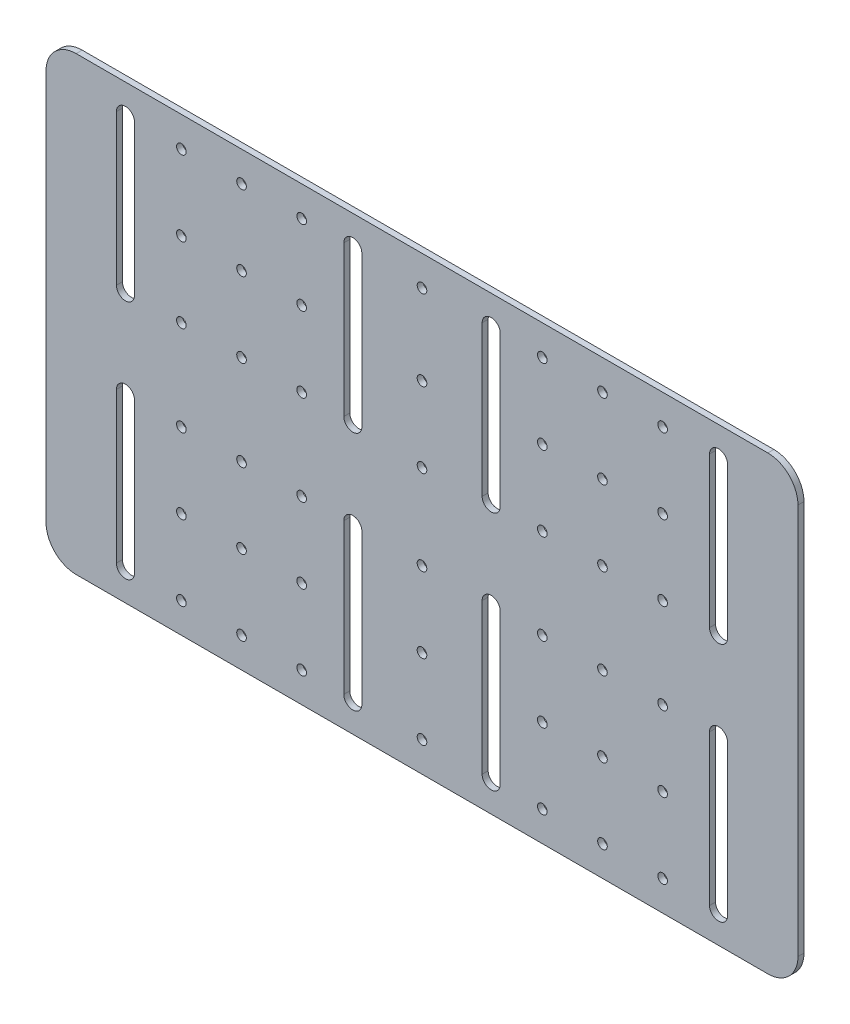
SolidWorks part; units mm, degrees
ref_plane "Front Plane" through (0, 0, 0) normal (0, 0, 1) x (1, 0, 0)
ref_plane "Top Plane" through (0, 0, 0) normal (0, 1, 0) x (1, 0, 0)
ref_plane "Right Plane" through (0, 0, 0) normal (1, 0, 0) x (0, 0, -1)
sketch "Sketch1" plane through (0, 0, 0) normal (0, 0, 1) x (1, 0, 0)
  line L1 (0, 0) -> (250, 0)
  line L2 (0, 0) -> (0, 150)
  line L3 (0, 150) -> (250, 150)
  line L4 (250, 0) -> (250, 150)
  dimension "D1" = 150
  dimension "D2" = 250
extrude "Boss-Extrude1" add sketch "Sketch1" along normal blind 2
sketch "Sketch2" plane through (0, 0, 2) normal (0, 0, 1) x (1, 0, 0)
  line L0 (0, 150) -> (25, 150) construction
  line L1 (250, 150) -> (0, 150) construction
  line L2 (25, 150) -> (25, 140) construction
  line L3 (25, 140) -> (225, 140) construction
  line L4 (225, 140) -> (225, 10) construction
  line L5 (225, 10) -> (25, 10) construction
  line L6 (25, 10) -> (25, 140) construction
  line L7 (25, 75) -> (225, 75) construction
  line L8 (250, 0) -> (250, 150) construction
  line L9 (0, 150) -> (0, 0) construction
  line L10 (125, 140) -> (125, 10) construction
  circle A0 centre (25, 140) radius 1.6
  circle A1 centre (45, 140) radius 1.6
  circle A11 centre (45, 115) radius 1.6
  circle A21 centre (45, 90) radius 1.6
  circle A31 centre (25, 115) radius 1.6
  circle A32 centre (25, 90) radius 1.6
  circle A33 centre (65, 140) radius 1.6
  circle A34 centre (65, 115) radius 1.6
  circle A35 centre (65, 90) radius 1.6
  circle A36 centre (85, 140) radius 1.6
  circle A37 centre (85, 115) radius 1.6
  circle A38 centre (85, 90) radius 1.6
  circle A39 centre (165, 90) radius 1.6
  circle A40 centre (185, 90) radius 1.6
  circle A41 centre (205, 90) radius 1.6
  circle A42 centre (225, 90) radius 1.6
  circle A43 centre (225, 115) radius 1.6
  circle A44 centre (205, 115) radius 1.6
  circle A45 centre (185, 115) radius 1.6
  circle A46 centre (165, 115) radius 1.6
  circle A47 centre (165, 140) radius 1.6
  circle A48 centre (185, 140) radius 1.6
  circle A49 centre (205, 140) radius 1.6
  circle A50 centre (225, 140) radius 1.6
  dimension "D1" = 25
  dimension "D2" = 25
  dimension "D3" = 4
  dimension "D4" = 3
extrude "Cut-Extrude1" cut sketch "Sketch2" against normal blind 2
sketch "Sketch3" plane through (0, 0, 2) normal (0, 0, 1) x (1, 0, 0)
  line L0 (0, 75) -> (250, 75) construction
  line L1 (0, 150) -> (0, 0) construction
  line L2 (250, 0) -> (250, 150) construction
ref_plane "Plane1" through (0, 75, 0) normal (0, -1, 0) x (1, 0, 0)
mirror "Mirror1" about plane through (0, 75, 0) normal (0, -1, 0) of "Cut-Extrude1"
sketch "Sketch5" plane through (0, 0, 2) normal (0, 0, 1) x (1, 0, 0)
  line L0 (23.4, 140) -> (23.4, 90)
  line L1 (23.4, 140) -> (29.4, 140) construction
  line L2 (29.4, 140) -> (29.4, 90)
  line L3 (29.4, 90) -> (23.4, 90) construction
  line L4 (0, 75) -> (250, 75) construction
  line L5 (0, 150) -> (0, 0) construction
  line L6 (250, 0) -> (250, 150) construction
  line L7 (125, 150) -> (125, 0) construction
  line L8 (250, 150) -> (0, 150) construction
  line L9 (0, 0) -> (250, 0) construction
  line L10 (29.4, 10) -> (29.4, 60)
  line L11 (23.4, 10) -> (23.4, 60)
  line L12 (226.6, 10) -> (226.6, 60)
  line L13 (220.6, 10) -> (220.6, 60)
  line L14 (226.6, 140) -> (226.6, 90)
  line L15 (220.6, 140) -> (220.6, 90)
  circle A0 centre (25, 140) radius 1.6 construction
  circle A1 centre (25, 90) radius 1.6 construction
  arc A2 (29.4, 140) -> (23.4, 140) centre (26.4, 140) ccw
  arc A3 (23.4, 90) -> (29.4, 90) centre (26.4, 90) ccw
  arc A4 (23.4, 60) -> (29.4, 60) centre (26.4, 60) cw
  arc A5 (29.4, 10) -> (23.4, 10) centre (26.4, 10) cw
  arc A6 (220.6, 10) -> (226.6, 10) centre (223.6, 10) ccw
  arc A7 (226.6, 60) -> (220.6, 60) centre (223.6, 60) ccw
  arc A8 (220.6, 140) -> (226.6, 140) centre (223.6, 140) cw
  arc A9 (226.6, 90) -> (220.6, 90) centre (223.6, 90) cw
extrude "Cut-Extrude2" cut sketch "Sketch5" against normal blind 2 contours A3 L2 A2 L0 | A4 L10 A5 L11 | L14 A9 L15 A8 | L12 A7 L13 A6
sketch "Sketch6" plane through (0, 0, 2) normal (0, 0, 1) x (1, 0, 0)
  line L0 (125, 150) -> (125, 0) construction
  line L1 (250, 150) -> (0, 150) construction
  line L2 (0, 0) -> (250, 0) construction
ref_plane "Plane2" through (125, 0, 0) normal (-1, 0, 0) x (0, -1, 0)
sketch "Sketch10" plane through (0, 0, 2) normal (0, 0, 1) x (1, 0, 0)
  line L0 (85, 140) -> (165, 140) construction
  line L1 (125, 140) -> (125, 0) construction
  line L2 (0, 0) -> (250, 0) construction
  line L3 (125, 140) -> (125, 113.2924) construction
  line L4 (125, 113.2924) -> (125, 88.2924) construction
  line L5 (85, 10) -> (125, 10) construction
  line L6 (125, 10) -> (125, 35) construction
  line L7 (125, 35) -> (125, 60) construction
  circle A1 centre (125, 140) radius 1.6
  circle A3 centre (125, 35) radius 1.6
  circle A4 centre (125, 60) radius 1.6
  circle A5 centre (125, 88.2924) radius 1.6
  circle A6 centre (125, 113.2924) radius 1.6
  circle A7 centre (125, 10) radius 1.6
extrude "Cut-Extrude7" cut sketch "Sketch10" against normal through all
sketch "Sketch11" plane through (0, 0, 2) normal (0, 0, 1) x (1, 0, 0)
  line L0 (83.4, 140) -> (99, 140) construction
  line L2 (99, 140) -> (99, 90)
  line L5 (105, 140) -> (105, 90)
  line L7 (125, 150) -> (125, 0) construction
  line L8 (250, 150) -> (0, 150) construction
  line L9 (0, 0) -> (250, 0) construction
  line L10 (0, 75) -> (250, 75) construction
  line L11 (0, 150) -> (0, 0) construction
  line L12 (250, 0) -> (250, 150) construction
  circle A0 centre (45, 140) radius 1.6 construction
  circle A1 centre (85, 140) radius 1.6 construction
  arc A2 (105, 140) -> (99, 140) centre (102, 140) ccw
  arc A3 (99, 90) -> (105, 90) centre (102, 90) ccw
  dimension "D1" = 15.6
extrude "Cut-Extrude8" cut sketch "Sketch11" against normal through all
sketch "Sketch12" plane through (0, 0, 2) normal (0, 0, 1) x (1, 0, 0)
  line L0 (125, 150) -> (125, 0) construction
  line L1 (250, 150) -> (0, 150) construction
  line L2 (0, 0) -> (250, 0) construction
ref_plane "Plane3" through (125, 0, 0) normal (-1, 0, 0) x (0, -1, 0)
sketch "Sketch13" plane through (0, 0, 2) normal (0, 0, 1) x (1, 0, 0)
  line L0 (0, 75) -> (250, 75) construction
  line L1 (0, 150) -> (0, 0) construction
  line L2 (250, 0) -> (250, 150) construction
ref_plane "Plane4" through (0, 75, 0) normal (0, -1, 0) x (1, 0, 0)
mirror "Mirror5" about plane through (0, 75, 0) normal (0, -1, 0) of "Cut-Extrude8" second plane through (125, 0, 0) second plane normal (-1, 0, 0)
fillet "Fillet1" radius 10 4 edges at (0, 0, 1) (250, 0, 1) (250, 150, 1) (0, 150, 1)
